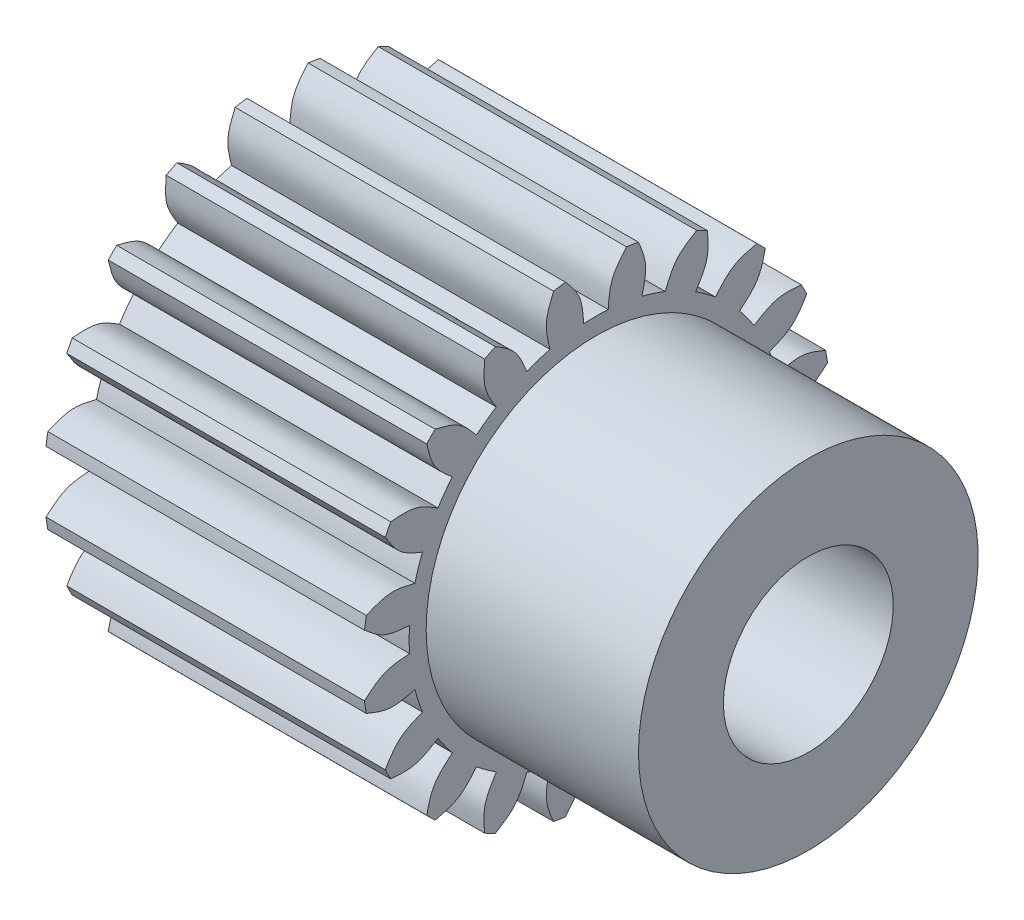
SolidWorks part; units mm, degrees
ref_plane "Front" through (0, 0, 0) normal (0, 0, 1) x (1, 0, 0)
ref_plane "Top" through (0, 0, 0) normal (0, 1, 0) x (1, 0, 0)
ref_plane "Right" through (0, 0, 0) normal (1, 0, 0) x (0, 0, -1)
sketch "Ritning 1" plane through (0, 0, 0) normal (0, 0, 1) x (1, 0, 0)
  line L0 (-12.5, -5.5) -> (12.5, -5.5) construction
  line L1 (-12.5, -1.5) -> (12.5, -1.5)
  line L2 (12.5, -1.5) -> (12.5, 2.5)
  line L3 (12.5, 2.5) -> (2.5, 2.5)
  line L4 (2.5, 2.5) -> (2.5, 5.5)
  line L5 (2.5, 5.5) -> (-12.5, 5.5)
  line L6 (-12.5, 5.5) -> (-12.5, -1.5)
  line L7 (-12.5, -1.5) -> (-12.5, -5.5) construction
  line L8 (12.5, -5.5) -> (12.5, -1.5) construction
  line L9 (-12.5, -5.5) -> (7.5, -5.5) construction
  dimension "D1" = 2.5
  dimension "D2" = 12.5
  dimension "D3" = 12.5
  dimension "D4" = 2.5
  dimension "D5" = 5.5
  dimension "D6" = 1.5
revolve "Kugghjulsämne" add sketch "Ritning 1" angle 360 about L0
sketch "Ritning 2" plane through (-12.5, 0, 0) normal (-1, 0, 0) x (0, 0, 1)
  line L0 (0, -5.5) -> (0, 5.5) construction
  line L1 (1.4409, 5.4052) -> (0, 6.8461)
  line L2 (-1.4409, 5.4052) -> (0, 6.8461)
  line L3 (0, -5.5) -> (2.0324, -5.5) construction
  arc A0 (0.5759, 3.2811) -> (-0.5759, 3.2811) centre (0, -5.5) ccw
  circle A1 centre (0, -5.5) radius 11 construction
  spline S0 degree 3 poles (1.4409, 5.4052) (1.1853, 5.1085) (0.66, 4.4987) (0.6045, 3.6942) (0.5759, 3.2811) knots 0 0 0 0 0.48648 1 1 1 1
  spline S1 degree 3 poles (-1.4409, 5.4052) (-1.1853, 5.1085) (-0.66, 4.4987) (-0.6045, 3.6942) (-0.5759, 3.2811) knots 0 0 0 0 0.48648 1 1 1 1
  dimension "D1" = 8.8
  dimension "D2" = 0.5759
  dimension "D3" = 0.7854
  dimension "D4" = 1.4409
  dimension "D5" = 9.9691
  dimension "D6" = 0.7854
  dimension "D7" = 10.9052
extrude "Kugglucka" cut sketch "Ritning 2" against normal up to surface (15 mm away) up to face at (2.5, -5.5, 11)
pattern_circular "CirPattern" count 20 over 360 about axis through (-12.5, -5.5, 0) along (-1, 0, 0) of "Kugglucka"
